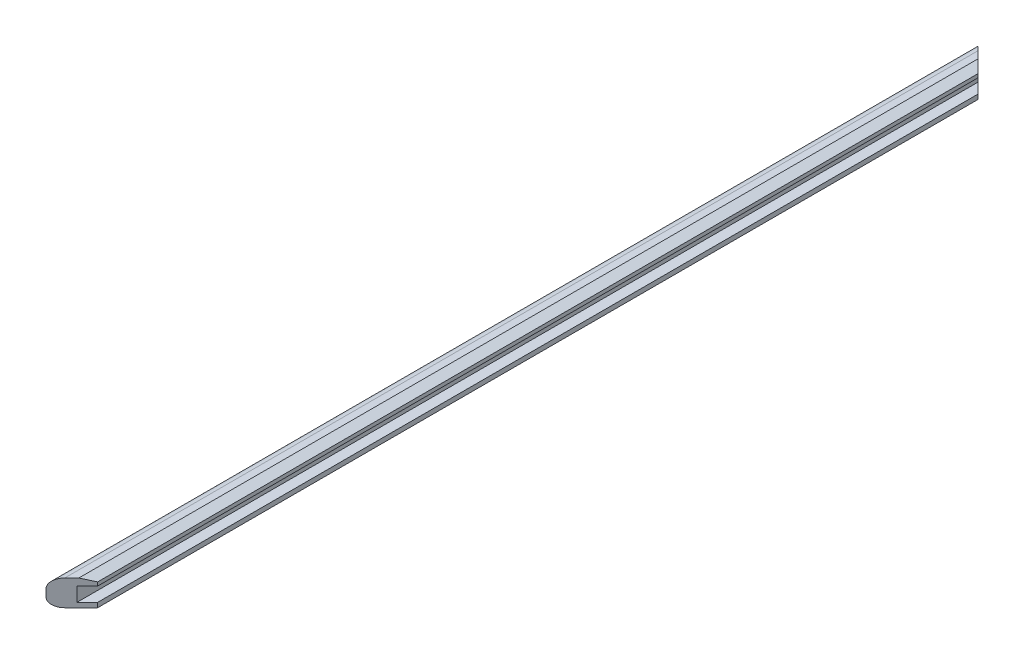
SolidWorks part; units mm, degrees
ref_plane "Front" through (0, 0, 0) normal (0, 0, 1) x (1, 0, 0)
ref_plane "Top" through (0, 0, 0) normal (0, 1, 0) x (1, 0, 0)
ref_plane "Right" through (0, 0, 0) normal (1, 0, 0) x (0, 0, -1)
sketch "Sketch1" plane through (0, 0, 0) normal (0, 0, 1) x (1, 0, 0)
  line L1 (-17.4625, -17.4625) -> (17.4625, -17.4625)
  line L2 (-17.4625, -17.4625) -> (-17.4625, 17.4625)
  line L3 (-17.4625, 17.4625) -> (17.4625, 17.4625)
  line L4 (17.4625, -17.4625) -> (17.4625, 17.4625)
  line L5 (-17.4625, -17.4625) -> (17.4625, 17.4625) construction
  line L6 (-17.4625, 17.4625) -> (17.4625, -17.4625) construction
  point P0 (0, 0)
  dimension "D1" = 34.925
extrude "Boss-Extrude1" add sketch "Sketch1" against normal blind 1320.8
sketch "Sketch2" plane through (0, 0, 0) normal (0, 0, 1) x (1, 0, 0)
  line L0 (17.4625, -17.4625) -> (17.4625, 17.4625) construction
  line L1 (17.4625, 7.9375) -> (3.4925, 7.9375)
  line L2 (17.4625, 7.9375) -> (17.4625, -11.1125)
  line L3 (17.4625, -11.1125) -> (3.4925, -11.1125)
  line L4 (3.4925, 7.9375) -> (3.4925, -11.1125)
  line L5 (17.4625, 17.4625) -> (-17.4625, 17.4625) construction
  dimension "D1" = 19.05
  dimension "D2" = 9.525
  dimension "D3" = 13.97
extrude "Cut-Extrude1" cut sketch "Sketch2" against normal through all
fillet "Fillet1" radius 12.7 2 edges at (-17.4625, -17.4625, -660.4) (-17.4625, 17.4625, -660.4)
chamfer "Chamfer1" distance 12.7 angle 20 1 edges at (17.4625, 17.4625, -660.4)
sketch "Sketch3" plane through (0, 17.4625, 0) normal (0, 1, 0) x (1, 0, 0)
  line L0 (-17.4625, 0) -> (17.4625, 34.925)
  line L2 (17.4625, 1320.8) -> (17.4625, 0) construction
  line L3 (17.4625, 34.925) -> (17.4625, 0)
  line L4 (17.4625, 0) -> (-17.4625, 0)
  line L5 (-17.4625, 1261.11) -> (17.4625, 1226.185)
  line L6 (-17.4625, 0) -> (-17.4625, 1320.8) construction
  line L7 (17.4625, 1226.185) -> (-17.4625, 1226.185) construction
  line L8 (-17.4625, 1226.185) -> (-17.4625, 1261.11) construction
  line L9 (-17.4625, 1261.11) -> (-17.4625, 1320.8)
  line L10 (-17.4625, 1320.8) -> (17.4625, 1320.8)
  line L11 (17.4625, 1320.8) -> (17.4625, 1226.185)
  line L12 (3.4925, 20.955) -> (3.4925, 1240.155) construction
  line L13 (3.4925, 1320.8) -> (3.4925, 0) construction
  dimension "D1" = 45
  dimension "D2" = 45
  dimension "D3" = 1219.2
extrude "Cut-Extrude2" cut sketch "Sketch3" against normal through all
